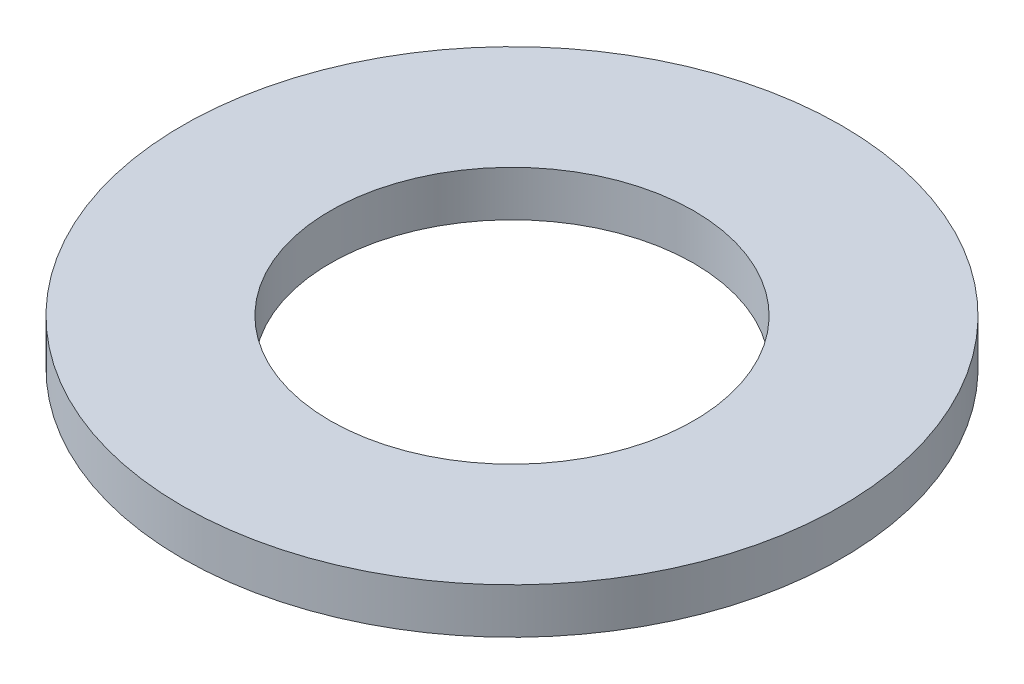
SolidWorks part; units mm, degrees
ref_plane "Front Plane" through (0, 0, 0) normal (0, 0, 1) x (1, 0, 0)
ref_plane "Top Plane" through (0, 0, 0) normal (0, 1, 0) x (1, 0, 0)
ref_plane "Right Plane" through (0, 0, 0) normal (1, 0, 0) x (0, 0, -1)
sketch "Sketch1" plane through (0, 0, 0) normal (0, 1, 0) x (1, 0, 0)
  circle A0 centre (0, 0) radius 14.5
  circle A1 centre (0, 0) radius 8
  dimension "D1" = 29
  dimension "D2" = 16
extrude "Boss-Extrude1" add sketch "Sketch1" along normal blind 2
